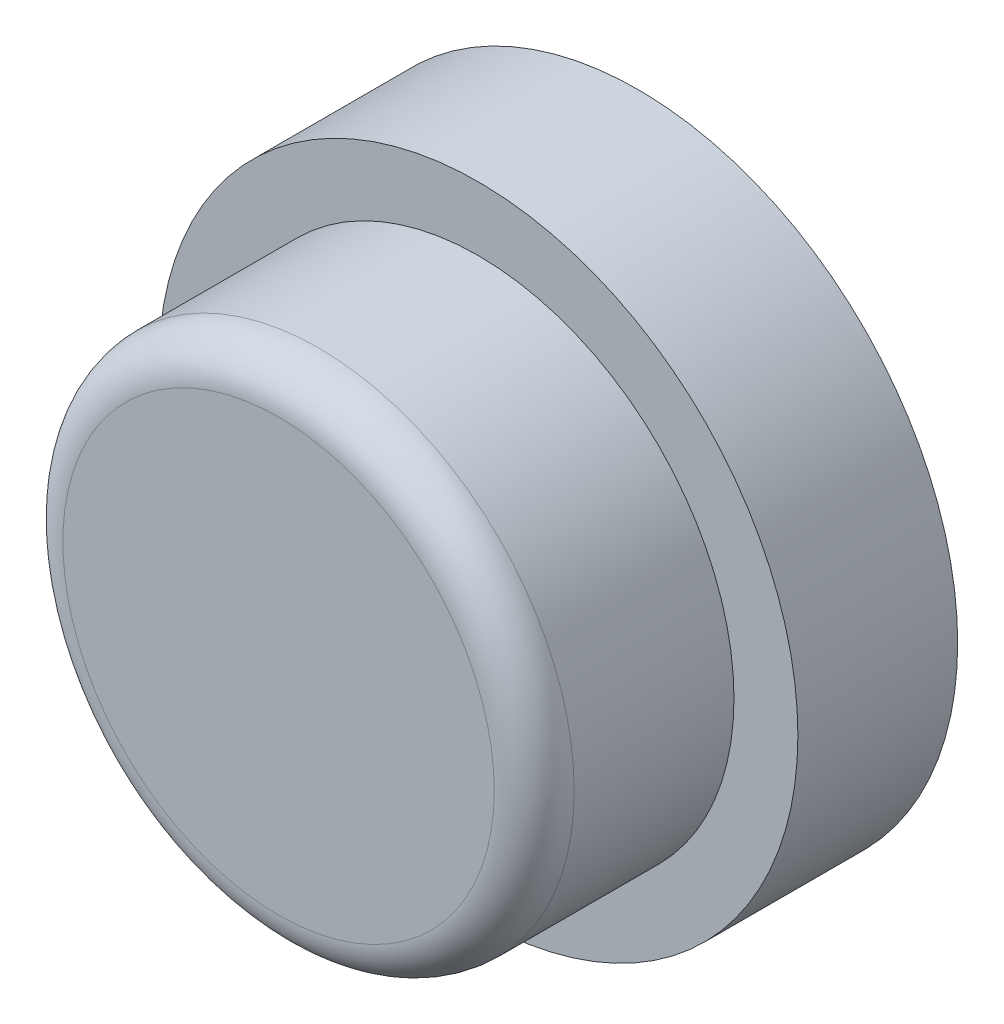
SolidWorks part; units mm, degrees
material "AISI 316 Stainless Steel Sheet (SS)"
ref_plane "Front Plane" through (0, 0, 0) normal (0, 0, 1) x (1, 0, 0)
ref_plane "Top Plane" through (0, 0, 0) normal (0, 1, 0) x (1, 0, 0)
ref_plane "Right Plane" through (0, 0, 0) normal (1, 0, 0) x (0, 0, -1)
sketch "Sketch1" plane through (0, 0, 0) normal (0, 1, 0) x (1, 0, 0)
  line L0 (0, 21.6762) -> (0, 11) construction
  line L1 (0, 0) -> (5.4, 0)
  line L2 (6.4, 1) -> (6.4, 5)
  line L3 (6.4, 5) -> (8, 5)
  line L4 (8, 5) -> (8, 9)
  line L5 (8, 9) -> (2.8284, 9)
  line L6 (0, 4) -> (0, -8.8837) construction
  line L7 (0, 0) -> (0, 11)
  arc A0 (2.8284, 9) -> (0, 11) centre (0, 8) ccw
  arc A1 (6.4, 1) -> (5.4, 0) centre (5.4, 1) cw
  point P16 (6.4, 0)
  dimension "D1" = 6
  dimension "D7" = 1
  dimension "D2" = 6.4
  dimension "D3" = 5
  dimension "D4" = 4
  dimension "D5" = 8
  dimension "D6" = 8
revolve "Revolve1" add sketch "Sketch1" angle 360 about L7
